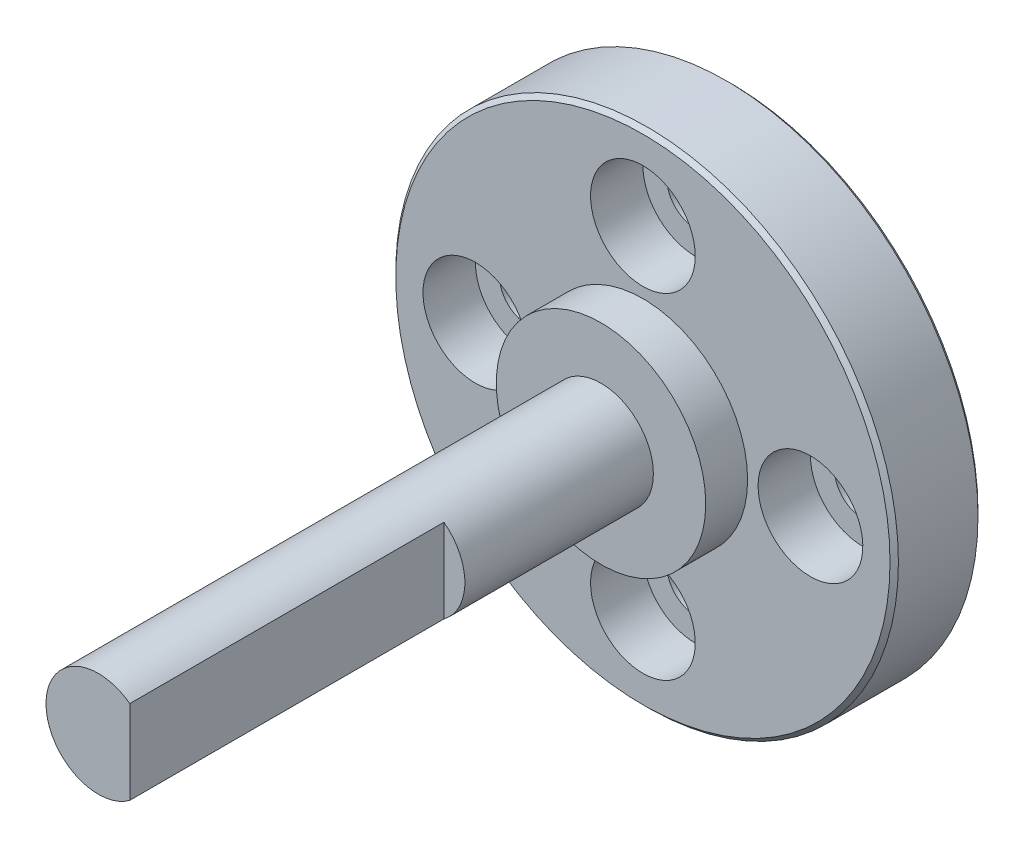
SolidWorks part; units mm, degrees
material "PA(尼龙6)"
ref_plane "前视基准面" through (0, 0, 0) normal (0, 0, 1) x (1, 0, 0)
ref_plane "上视基准面" through (0, 0, 0) normal (0, 1, 0) x (1, 0, 0)
ref_plane "右视基准面" through (0, 0, 0) normal (1, 0, 0) x (0, 0, -1)
sketch "草图1" plane through (0, 0, 0) normal (0, 0, 1) x (1, 0, 0)
  circle A3 centre (0, 0) radius 3
  circle A4 centre (0, 0) radius 12
  point P7 (0, 0)
  dimension "D1" = 24
  dimension "D2" = 6
extrude "凸台-拉伸1" add sketch "草图1" along normal blind 4.2 contours A3 | A4 A3
sketch "草图2" plane through (0, 0, 4.2) normal (0, 0, 1) x (1, 0, 0)
  circle A0 centre (0, 0) radius 5
  dimension "D1" = 10
extrude "凸台-拉伸2" add sketch "草图2" along normal blind 2
hole_wizard "M2.5 六角圆柱头螺钉的柱形沉头孔1" positions "草图8" profile "草图9" counterbore size "M2.5" standard "GB" end condition through all
sketch "草图8" plane through (0, 0, 4.2) normal (0, 0, 1) x (1, 0, 0)
  line L0 (0, 0) -> (0, 8) construction
  point P0 (0, 8)
  dimension "D1" = 8
sketch "草图9" plane through (0, 8, 4.2) normal (1, 0, 0) x (0, -1, 0)
  line L0 (0, 0) -> (0, 4.2)
  line L1 (0, 4.2) -> (1.35, 4.2)
  line L3 (1.35, 4.2) -> (1.35, 2.5)
  line L4 (1.35, 2.5) -> (2.5, 2.5)
  line L5 (2.5, 2.5) -> (2.5, 0)
  line L7 (2.5, 0) -> (0, 0)
  line L11 (0, -6.35) -> (0, 107.95) construction
  dimension "通孔孔直径" = 2.7
  dimension "通孔孔深度" = 4.2
  dimension "柱形沉头孔直径" = 5
  dimension "柱形沉头孔深度" = 2.5
pattern_circular "阵列(圆周)1" count 4 over 360 about axis through (0, 0, 0) along (0, 0, 1) of "M2.5 六角圆柱头螺钉的柱形沉头孔1"
chamfer "倒角3" distance 0.2 angle 45 2 edges at (12, 0, 4.2) (12, 0, 0)
sketch "草图12" plane through (0, 0, 4.2) normal (0, 0, 1) x (1, 0, 0)
  circle A0 centre (0, 0) radius 2.5
  dimension "D1" = 5
extrude "轴" add sketch "草图12" along normal blind 26
sketch "草图13" plane through (0, 0, 30.2) normal (0, 0, 1) x (1, 0, 0)
  line L0 (0, 0) -> (4.1196, 0) construction
  line L1 (1.5, 2.6158) -> (1.5, -2.6158)
  circle A0 centre (0, 0) radius 2.5 construction
  circle A1 centre (0, 0) radius 2.5
  point P6 (1.5, 0)
  circle M2 centre (0, 0) radius 2.5
  dimension "D1" = 1.5
extrude "切除-拉伸1" cut sketch "草图13" against normal blind 15 contours L0 L1 M2 | L1 L0 A1
